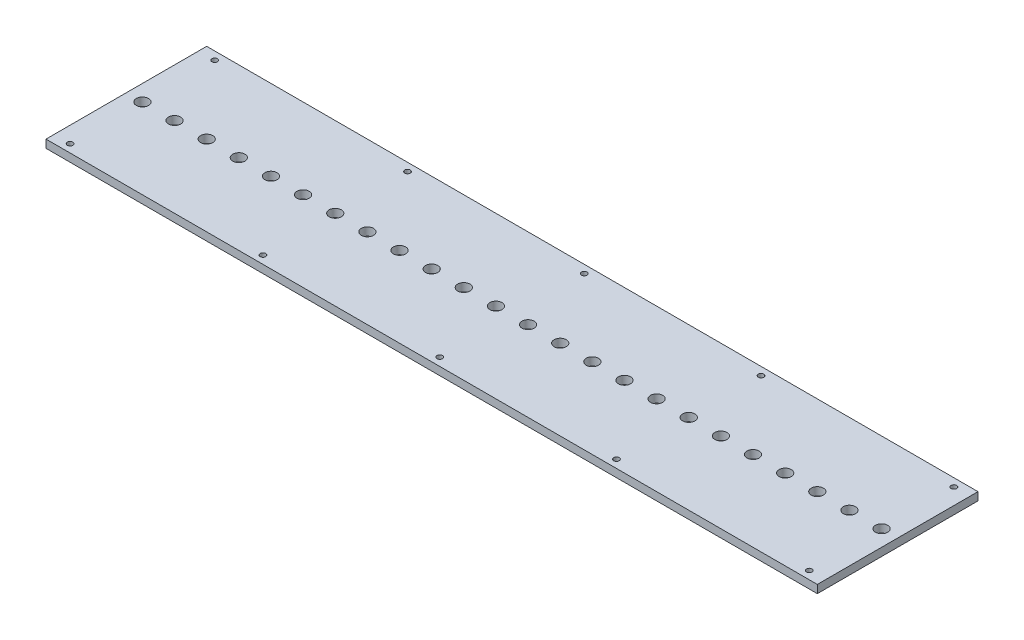
SolidWorks part; units mm, degrees
ref_plane "Front Plane" through (0, 0, 0) normal (0, 0, 1) x (1, 0, 0)
ref_plane "Top Plane" through (0, 0, 0) normal (0, 1, 0) x (1, 0, 0)
ref_plane "Right Plane" through (0, 0, 0) normal (1, 0, 0) x (0, 0, -1)
sketch "Sketch2" plane through (0, 0, 0) normal (0, 1, 0) x (1, 0, 0)
  line L0 (0, 0) -> (0, 127)
  line L1 (0, 127) -> (609.6, 127)
  line L2 (609.6, 127) -> (609.6, 0)
  line L3 (609.6, 0) -> (0, 0)
  circle A0 centre (12.7, 63.5) radius 4.826
  circle A1 centre (38.1, 63.5) radius 4.826
  circle A2 centre (63.5, 63.5) radius 4.826
  circle A3 centre (88.9, 63.5) radius 4.826
  circle A4 centre (114.3, 63.5) radius 4.826
  circle A5 centre (139.7, 63.5) radius 4.826
  circle A6 centre (165.1, 63.5) radius 4.826
  circle A7 centre (190.5, 63.5) radius 4.826
  circle A8 centre (215.9, 63.5) radius 4.826
  circle A9 centre (241.3, 63.5) radius 4.826
  circle A10 centre (266.7, 63.5) radius 4.826
  circle A11 centre (292.1, 63.5) radius 4.826
  circle A12 centre (317.5, 63.5) radius 4.826
  circle A13 centre (342.9, 63.5) radius 4.826
  circle A14 centre (368.3, 63.5) radius 4.826
  circle A15 centre (393.7, 63.5) radius 4.826
  circle A16 centre (419.1, 63.5) radius 4.826
  circle A17 centre (444.5, 63.5) radius 4.826
  circle A18 centre (469.9, 63.5) radius 4.826
  circle A19 centre (495.3, 63.5) radius 4.826
  circle A20 centre (520.7, 63.5) radius 4.826
  circle A21 centre (546.1, 63.5) radius 4.826
  circle A22 centre (571.5, 63.5) radius 4.826
  circle A23 centre (596.9, 63.5) radius 4.826
  dimension "D3" = 12.7
  dimension "D5" = 9.652
  dimension "D1" = 127
  dimension "D2" = 609.6
  dimension "D4" = 24
extrude "Boss-Extrude1" add sketch "Sketch2" along normal blind 6.35
sketch "Sketch3" plane through (0, 6.35, 0) normal (0, 1, 0) x (1, 0, 0)
  line L1 (12.7, 120.65) -> (596.9, 120.65) construction
  line L2 (596.9, 120.65) -> (596.9, 6.35) construction
  line L3 (596.9, 6.35) -> (12.7, 6.35) construction
  line L4 (12.7, 6.35) -> (12.7, 120.65) construction
  line L5 (165.1, 120.65) -> (165.1, 6.35) construction
  line L6 (304.8, 120.65) -> (304.8, 6.35) construction
  line L7 (444.5, 120.65) -> (444.5, 6.35) construction
  line L8 (0, 127) -> (0, 0) construction
  line L9 (0, 0) -> (609.6, 0) construction
  circle A0 centre (12.7, 120.65) radius 2.1828
  circle A1 centre (165.1, 120.65) radius 2.1828
  circle A2 centre (304.8, 120.65) radius 2.1828
  circle A3 centre (444.5, 120.65) radius 2.1828
  circle A4 centre (596.9, 120.65) radius 2.1828
  circle A5 centre (596.9, 6.35) radius 2.1828
  circle A6 centre (444.5, 6.35) radius 2.1828
  circle A7 centre (304.8, 6.35) radius 2.1828
  circle A8 centre (165.1, 6.35) radius 2.1828
  circle A9 centre (12.7, 6.35) radius 2.1828
  dimension "D1" = 12.7
  dimension "D8" = 4.3656
  dimension "D2" = 6.35
  dimension "D3" = 120.65
  dimension "D4" = 596.9
  dimension "D5" = 165.1
  dimension "D6" = 304.8
  dimension "D7" = 444.5
extrude "Cut-Extrude1" cut sketch "Sketch3" against normal up to surface (6.35 mm away) up to face at (520.7, 0, -58.674)
